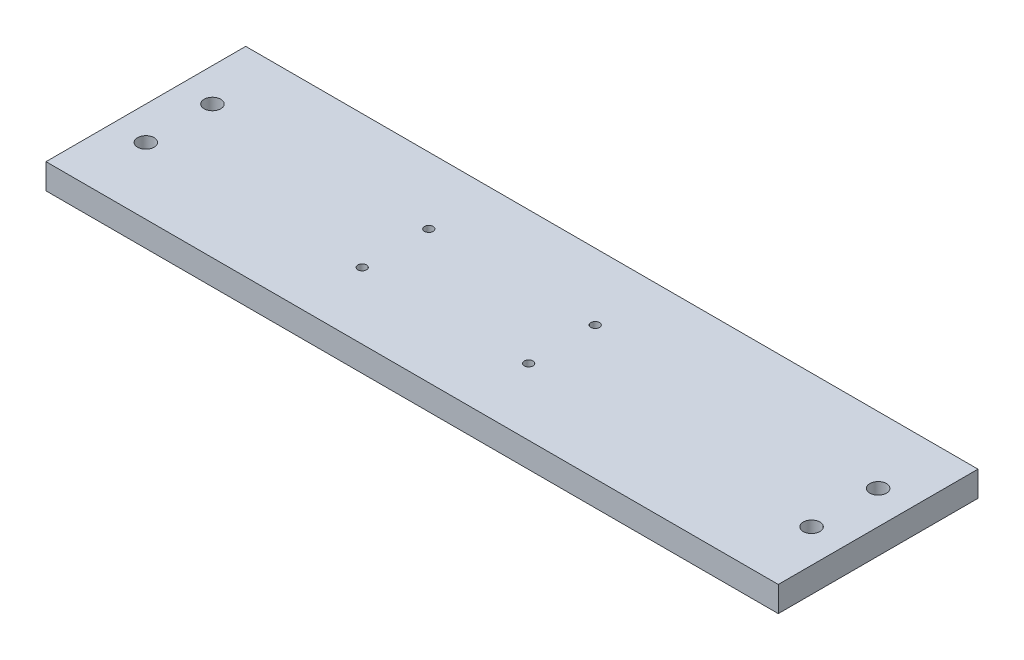
SolidWorks part; units mm, degrees
ref_plane "Front Plane" through (0, 0, 0) normal (0, 0, 1) x (1, 0, 0)
ref_plane "Top Plane" through (0, 0, 0) normal (0, 1, 0) x (1, 0, 0)
ref_plane "Right Plane" through (0, 0, 0) normal (1, 0, 0) x (0, 0, -1)
sketch "Sketch1" plane through (0, 0, 0) normal (0, 1, 0) x (1, 0, 0)
  line L1 (-139.7, 38.1) -> (139.7, 38.1)
  line L2 (-139.7, 38.1) -> (-139.7, -38.1)
  line L3 (-139.7, -38.1) -> (139.7, -38.1)
  line L4 (139.7, 38.1) -> (139.7, -38.1)
  line L5 (-139.7, 38.1) -> (139.7, -38.1) construction
  line L6 (-139.7, -38.1) -> (139.7, 38.1) construction
  point P0 (0, 0)
  dimension "D1" = 279.4
  dimension "D2" = 76.2
extrude "Boss-Extrude1" add sketch "Sketch1" along normal blind 9.652
sketch "Sketch2" plane through (0, 9.652, 0) normal (0, 1, 0) x (1, 0, 0)
  line L0 (-139.7, 38.1) -> (-139.7, -38.1) construction
  line L1 (-5.3086, 0) -> (5.3086, 0) construction
  circle A0 centre (-127, 12.7) radius 3.175
  circle A1 centre (-44.45, 12.7) radius 1.651
  circle A2 centre (19.05, 12.7) radius 1.651
  circle A3 centre (127, 12.7) radius 3.175
  circle A4 centre (127, -12.7) radius 3.175
  circle A5 centre (19.05, -12.7) radius 1.651
  circle A6 centre (-44.45, -12.7) radius 1.651
  circle A7 centre (-127, -12.7) radius 3.175
  point P8 (0, 0)
  point P9 (0, 0)
  dimension "D1" = 6.35
  dimension "D2" = 3.302
  dimension "D3" = 82.55
  dimension "D4" = 63.5
  dimension "D5" = 107.95
  dimension "D6" = 12.7
  dimension "D7" = 25.4
extrude "Cut-Extrude1" cut sketch "Sketch2" against normal blind 9.652
